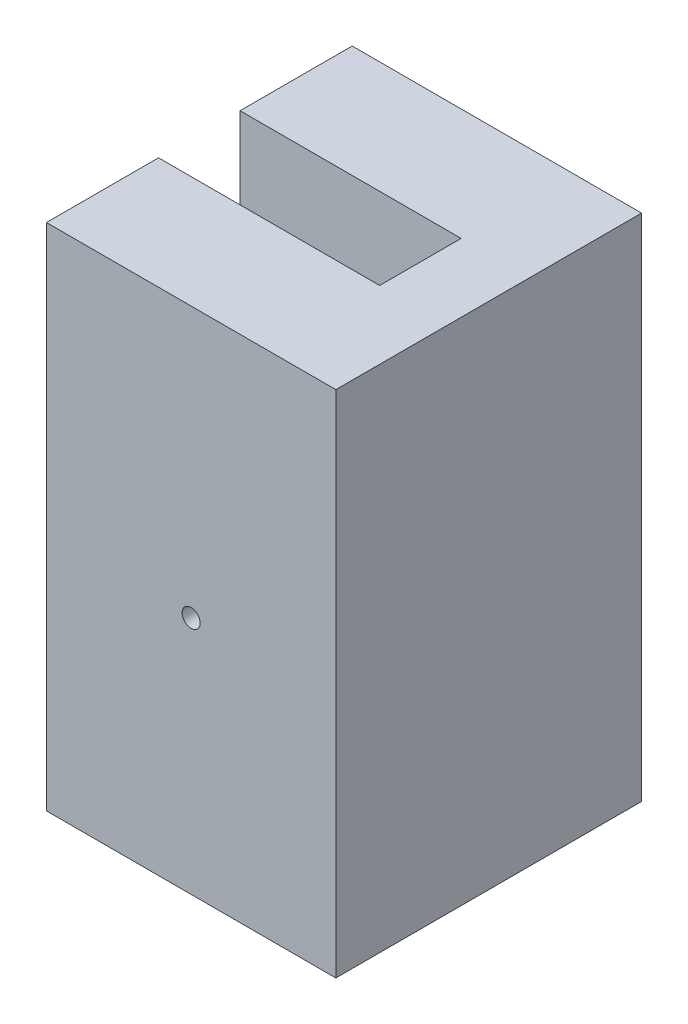
SolidWorks part; units mm, degrees
ref_plane "Front Plane" through (0, 0, 0) normal (0, 0, 1) x (1, 0, 0)
ref_plane "Top Plane" through (0, 0, 0) normal (0, 1, 0) x (1, 0, 0)
ref_plane "Right Plane" through (0, 0, 0) normal (1, 0, 0) x (0, 0, -1)
sketch "Sketch1" plane through (0, 0, 0) normal (0, 1, 0) x (1, 0, 0)
  line L1 (-18.034, 19.05) -> (18.034, 19.05)
  line L2 (-18.034, 19.05) -> (-18.034, -19.05)
  line L3 (-18.034, -19.05) -> (18.034, -19.05)
  line L4 (18.034, 19.05) -> (18.034, -19.05)
  line L5 (-18.034, 19.05) -> (18.034, -19.05) construction
  line L6 (-18.034, -19.05) -> (18.034, 19.05) construction
  point P0 (0, 0)
  dimension "D1" = 38.1
  dimension "D2" = 36.068
extrude "Boss-Extrude1" add sketch "Sketch1" along normal blind 63.5
sketch "Sketch3" plane through (0, 63.5, 0) normal (0, 1, 0) x (1, 0, 0)
  line L0 (18.034, -19.05) -> (18.034, 19.05) construction
  line L1 (-18.034, 5.08) -> (18.034, 5.08)
  line L2 (-18.034, 5.08) -> (-18.034, -5.08)
  line L3 (-18.034, -5.08) -> (18.034, -5.08)
  line L4 (18.034, 5.08) -> (18.034, -5.08)
  line L5 (-18.034, 5.08) -> (18.034, -5.08) construction
  line L6 (-18.034, -5.08) -> (18.034, 5.08) construction
  point P0 (0, 0)
  dimension "D1" = 10.16
extrude "Cut-Extrude1" cut sketch "Sketch3" against normal blind 38.1
sketch "Sketch4" plane through (0, 0, 0) normal (0, -1, 0) x (1, 0, 0)
  line L0 (18.034, 19.05) -> (18.034, -19.05) construction
  line L1 (-18.034, -8.5725) -> (18.034, -8.5725)
  line L2 (-18.034, -8.5725) -> (-18.034, 8.5725)
  line L3 (-18.034, 8.5725) -> (18.034, 8.5725)
  line L4 (18.034, -8.5725) -> (18.034, 8.5725)
  line L5 (-18.034, -8.5725) -> (18.034, 8.5725) construction
  line L6 (-18.034, 8.5725) -> (18.034, -8.5725) construction
  point P0 (0, 0)
  dimension "D1" = 17.145
extrude "Cut-Extrude2" cut sketch "Sketch4" against normal offset from surface (19.05 mm away) 6.35 up to face at (0, 25.4, 0)
sketch "Sketch5" plane through (0, 25.4, 0) normal (0, 1, 0) x (1, 0, 0)
  line L0 (18.034, 5.08) -> (-18.034, 5.08) construction
  line L1 (-0.635, -5.08) -> (0.635, -5.08)
  line L2 (-0.635, -5.08) -> (-0.635, 5.08)
  line L3 (-0.635, 5.08) -> (0.635, 5.08)
  line L4 (0.635, -5.08) -> (0.635, 5.08)
  line L5 (-0.635, -5.08) -> (0.635, 5.08) construction
  line L6 (-0.635, 5.08) -> (0.635, -5.08) construction
  line L7 (-18.034, -8.5725) -> (-18.034, 8.5725) construction
  line L8 (-0.635, 5.08) -> (-18.034, 5.08)
  line L9 (-0.635, 5.08) -> (-0.635, -5.08)
  line L10 (-0.635, -5.08) -> (-18.034, -5.08)
  line L11 (-18.034, 5.08) -> (-18.034, -5.08)
  line L13 (0.635, 5.08) -> (18.034, 5.08)
  line L14 (0.635, 5.08) -> (0.635, -5.08)
  line L15 (0.635, -5.08) -> (18.034, -5.08)
  line L16 (18.034, 5.08) -> (18.034, -5.08)
  point P0 (0, 0)
  line M10 (18.034, -5.08) -> (18.034, 5.08)
  line M11 (18.034, 5.08) -> (-18.034, 5.08)
  line M12 (-18.034, 5.08) -> (-18.034, -5.08)
  line M13 (-18.034, -5.08) -> (18.034, -5.08)
  dimension "D1" = 1.27
extrude "Cut-Extrude3" cut sketch "Sketch5" against normal through all contours L2 M13 M11 M12 | L4 M13 M10 M11
sketch "Sketch6" plane through (0, 0, -5.08) normal (0, 0, 1) x (1, 0, 0)
  line L0 (0.635, 25.4) -> (-0.635, 25.4) construction
  line L1 (0, 0) -> (0, 29.845) construction
  circle A0 centre (0, 29.845) radius 1.125
  dimension "D1" = 2.25
  dimension "D2" = 4.445
extrude "Cut-Extrude4" cut sketch "Sketch6" against normal through all both and the other way through all
sketch "Sketch7" plane through (0, 63.5, 0) normal (0, 1, 0) x (1, 0, 0)
  line L0 (18.034, 19.05) -> (18.034, -19.05)
  line L1 (18.034, 19.05) -> (9.525, 19.05)
  line L2 (18.034, -19.05) -> (9.525, -19.05)
  line L3 (9.525, 19.05) -> (9.525, -19.05)
  line L5 (0.635, -5.08) -> (0.635, 5.08) construction
  dimension "D1" = 8.89
sketch "Sketch8" plane through (0.635, 0, 0) normal (1, 0, 0) x (0, 0, -1)
  line L0 (-5.08, 19.05) -> (-5.08, 25.4)
  line L1 (-5.08, 19.05) -> (5.08, 19.05)
  line L2 (-5.08, 25.4) -> (5.08, 25.4)
  line L3 (5.08, 19.05) -> (5.08, 25.4)
extrude "Boss-Extrude2" add sketch "Sketch7" against normal up to surface (63.5 mm away) up to face at (0, 0, 13.8113)
extrude "Boss-Extrude3" add sketch "Sketch8" along normal up to surface (8.89 mm away) up to face at (9.525, 25.4, 0)
